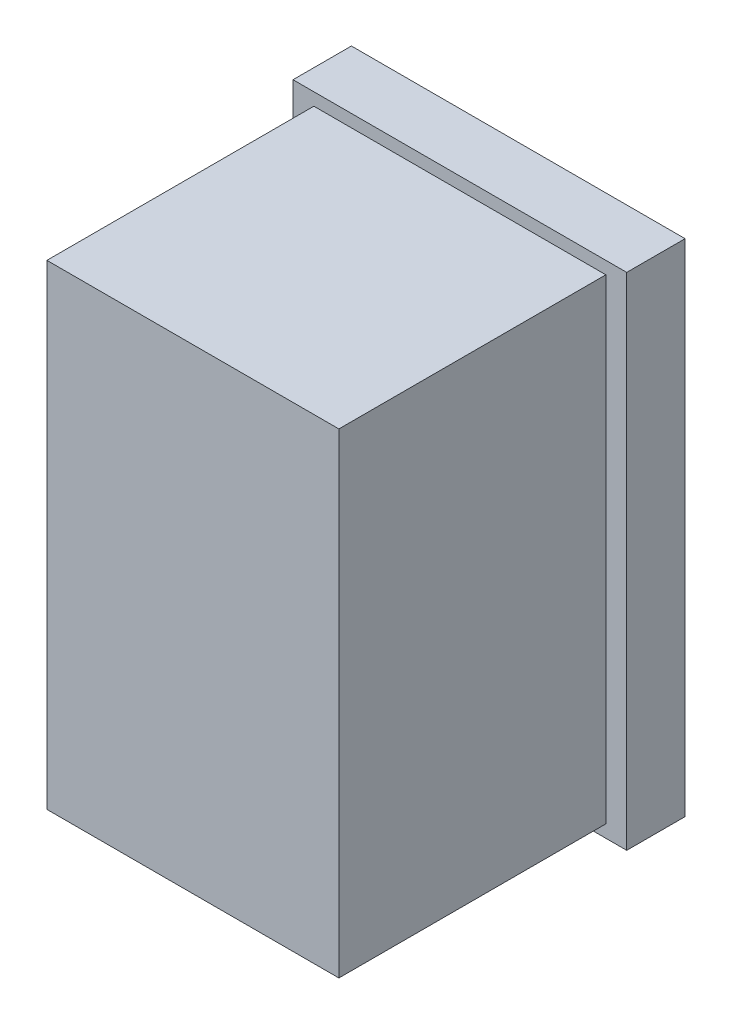
SolidWorks part; units mm, degrees
material "ABS"
ref_plane "Front Plane" through (0, 0, 0) normal (0, 0, 1) x (1, 0, 0)
ref_plane "Top Plane" through (0, 0, 0) normal (0, 1, 0) x (1, 0, 0)
ref_plane "Right Plane" through (0, 0, 0) normal (1, 0, 0) x (0, 0, -1)
sketch "Sketch1" plane through (0, 0, 0) normal (0, 0, 1) x (1, 0, 0)
  line L1 (-4.445, 7.239) -> (4.445, 7.239)
  line L2 (-4.445, 7.239) -> (-4.445, -7.239)
  line L3 (-4.445, -7.239) -> (4.445, -7.239)
  line L4 (4.445, 7.239) -> (4.445, -7.239)
  line L5 (-4.445, 7.239) -> (4.445, -7.239) construction
  line L6 (-4.445, -7.239) -> (4.445, 7.239) construction
  point P0 (0, 0)
  dimension "D1" = 8.89
  dimension "D2" = 14.478
extrude "Boss-Extrude1" add sketch "Sketch1" along normal blind 8.128
sketch "Sketch2" plane through (0, 0, 0) normal (0, 0, -1) x (-1, 0, 0)
  line L1 (-5.08, 7.62) -> (5.08, 7.62)
  line L2 (-5.08, 7.62) -> (-5.08, -7.62)
  line L3 (-5.08, -7.62) -> (5.08, -7.62)
  line L4 (5.08, 7.62) -> (5.08, -7.62)
  line L5 (-5.08, 7.62) -> (5.08, -7.62) construction
  line L6 (-5.08, -7.62) -> (5.08, 7.62) construction
  point P0 (0, 0)
  dimension "D1" = 15.24
  dimension "D2" = 10.16
extrude "Boss-Extrude2" add sketch "Sketch2" along normal blind 1.778
